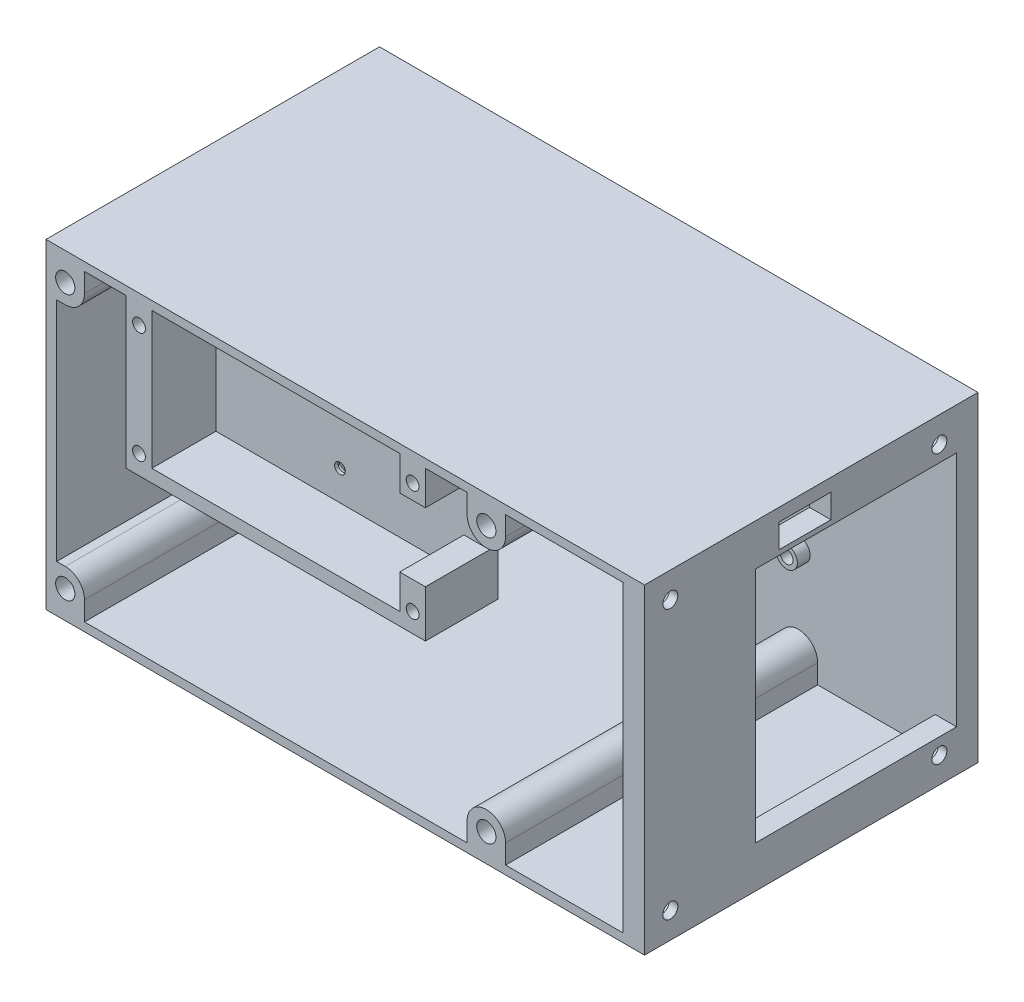
SolidWorks part; units mm, degrees
ref_plane "Płaszczyzna przednia" through (0, 0, 0) normal (0, 0, 1) x (1, 0, 0)
ref_plane "Płaszczyzna górna" through (0, 0, 0) normal (0, 1, 0) x (1, 0, 0)
ref_plane "Płaszczyzna prawa" through (0, 0, 0) normal (1, 0, 0) x (0, 0, -1)
sketch "Szkic1" plane through (0, 0, 0) normal (0, 0, 1) x (1, 0, 0)
  line L0 (0, 75) -> (140, 75)
  line L1 (140, 75) -> (140, 0)
  line L2 (140, 0) -> (0, 0)
  line L3 (0, 0) -> (0, 75)
  line L4 (3, 62.75) -> (3, 12.25) construction
  line L5 (3, 12.25) -> (73, 12.25) construction
  line L6 (73, 12.25) -> (73, 62.75) construction
  line L7 (73, 62.75) -> (3, 62.75) construction
  line L12 (70, 75) -> (70, 0) construction
  line L13 (0, 37.5) -> (140, 37.5) construction
  line L14 (88, 50.2) -> (88, 24.8) construction
  line L15 (88, 24.8) -> (105.78, 24.8) construction
  line L16 (105.78, 24.8) -> (105.78, 50.2) construction
  line L17 (105.78, 50.2) -> (88, 50.2) construction
  line L18 (96.89, 50.2) -> (96.89, 24.8) construction
  circle A0 centre (6.6, 58.05) radius 2
  circle A1 centre (6.6, 16.95) radius 2
  circle A2 centre (69.3, 58.05) radius 2
  circle A3 centre (69.3, 16.95) radius 2
  circle A4 centre (5.77, 45.35) radius 1 construction
  circle A5 centre (46.43, 45.35) radius 1 construction
  circle A6 centre (46.43, 30.09) radius 1 construction
  circle A7 centre (5.77, 30.09) radius 1 construction
  circle A17 centre (90.54, 47.66) radius 1.5
  circle A18 centre (103.24, 47.66) radius 1.5
  circle A19 centre (103.24, 27.34) radius 1.5
  circle A20 centre (90.54, 27.34) radius 1.5
  point P25 (73, 37.5)
  point P30 (88, 37.5)
  dimension "D5" = 4
  dimension "D9" = 2
  dimension "D17" = 3
  dimension "D21" = 3
  dimension "D3" = 70
  dimension "D4" = 50.5
  dimension "D6" = 3.6
  dimension "D7" = 4.7
  dimension "D8" = 4.7
  dimension "D10" = 3.7
  dimension "D11" = 4.7
  dimension "D12" = 43.43
  dimension "D13" = 2.77
  dimension "D14" = 17.4
  dimension "D15" = 32.66
  dimension "D16" = 140
  dimension "D18" = 25.4
  dimension "D19" = 17.78
  dimension "D20" = 15
  dimension "D22" = 6.35
  dimension "D23" = 10.16
  dimension "D26" = 75
extrude "Dodanie-wyciągnięcie1" add sketch "Szkic1" along normal blind 5
sketch "Szkic2" plane through (0, 0, 0) normal (0, 0, -1) x (-1, 0, 0)
  line L0 (-72.35, 59.8109) -> (-69.3, 61.5718)
  line L1 (-69.3, 61.5718) -> (-66.25, 59.8109)
  line L2 (-66.25, 59.8109) -> (-66.25, 56.2891)
  line L3 (-66.25, 56.2891) -> (-69.3, 54.5282)
  line L4 (-69.3, 54.5282) -> (-72.35, 56.2891)
  line L5 (-72.35, 56.2891) -> (-72.35, 59.8109)
  line L6 (-69.3, 58.05) -> (-69.3, 16.95) construction
  line L7 (-69.3, 16.95) -> (-6.6, 16.95) construction
  line L8 (-6.6, 16.95) -> (-6.6, 58.05) construction
  line L9 (-6.6, 58.05) -> (-69.3, 58.05) construction
  line L10 (-69.3, 37.5) -> (-6.6, 37.5) construction
  line L11 (-37.95, 58.05) -> (-37.95, 16.95) construction
  line L12 (-6.6, 54.5282) -> (-3.55, 56.2891)
  line L13 (-9.65, 56.2891) -> (-6.6, 54.5282)
  line L14 (-9.65, 59.8109) -> (-9.65, 56.2891)
  line L15 (-6.6, 61.5718) -> (-9.65, 59.8109)
  line L16 (-3.55, 59.8109) -> (-6.6, 61.5718)
  line L17 (-3.55, 56.2891) -> (-3.55, 59.8109)
  line L18 (-9.65, 18.7109) -> (-6.6, 20.4718)
  line L19 (-9.65, 15.1891) -> (-9.65, 18.7109)
  line L20 (-6.6, 13.4282) -> (-9.65, 15.1891)
  line L21 (-3.55, 15.1891) -> (-6.6, 13.4282)
  line L22 (-3.55, 18.7109) -> (-3.55, 15.1891)
  line L23 (-6.6, 20.4718) -> (-3.55, 18.7109)
  line L24 (-69.3, 20.4718) -> (-72.35, 18.7109)
  line L25 (-66.25, 18.7109) -> (-69.3, 20.4718)
  line L26 (-66.25, 15.1891) -> (-66.25, 18.7109)
  line L27 (-69.3, 13.4282) -> (-66.25, 15.1891)
  line L28 (-72.35, 15.1891) -> (-69.3, 13.4282)
  line L29 (-72.35, 18.7109) -> (-72.35, 15.1891)
  line L84 (-70, 75) -> (-70, 0) construction
  line L85 (-140, 75) -> (0, 75) construction
  line L86 (0, 0) -> (-140, 0) construction
  line L88 (-140, 37.5) -> (0, 37.5) construction
  line L89 (-140, 0) -> (-140, 75) construction
  line L90 (0, 75) -> (0, 0) construction
  line L91 (-93.09, 49.1322) -> (-90.54, 50.6045)
  line L92 (-90.54, 50.6045) -> (-87.99, 49.1322)
  line L93 (-87.99, 49.1322) -> (-87.99, 46.1878)
  line L94 (-87.99, 46.1878) -> (-90.54, 44.7155)
  line L95 (-90.54, 44.7155) -> (-93.09, 46.1878)
  line L96 (-93.09, 46.1878) -> (-93.09, 49.1322)
  line L97 (-90.54, 47.66) -> (-103.24, 47.66) construction
  line L98 (-103.24, 47.66) -> (-103.24, 27.34) construction
  line L99 (-103.24, 27.34) -> (-90.54, 27.34) construction
  line L100 (-90.54, 27.34) -> (-90.54, 47.66) construction
  line L102 (-96.89, 47.66) -> (-96.89, 27.34) construction
  line L104 (-103.24, 44.7155) -> (-100.69, 46.1878)
  line L105 (-105.79, 46.1878) -> (-103.24, 44.7155)
  line L106 (-105.79, 49.1322) -> (-105.79, 46.1878)
  line L107 (-103.24, 50.6045) -> (-105.79, 49.1322)
  line L108 (-100.69, 49.1322) -> (-103.24, 50.6045)
  line L109 (-100.69, 46.1878) -> (-100.69, 49.1322)
  line L110 (-90.54, 30.2845) -> (-93.09, 28.8122)
  line L111 (-87.99, 28.8122) -> (-90.54, 30.2845)
  line L112 (-90.54, 24.3955) -> (-87.99, 25.8678)
  line L113 (-87.99, 25.8678) -> (-87.99, 28.8122)
  line L114 (-93.09, 25.8678) -> (-90.54, 24.3955)
  line L115 (-93.09, 28.8122) -> (-93.09, 25.8678)
  line L116 (-105.79, 25.8678) -> (-105.79, 28.8122)
  line L117 (-103.24, 24.3955) -> (-105.79, 25.8678)
  line L118 (-100.69, 25.8678) -> (-103.24, 24.3955)
  line L119 (-100.69, 28.8122) -> (-100.69, 25.8678)
  line L120 (-103.24, 30.2845) -> (-100.69, 28.8122)
  line L121 (-105.79, 28.8122) -> (-103.24, 30.2845)
  circle A0 centre (-69.3, 58.05) radius 3.05 construction
  circle A1 centre (-69.3, 58.05) radius 2 construction
  circle A2 centre (-69.3, 16.95) radius 2 construction
  circle A3 centre (-6.6, 16.95) radius 2 construction
  circle A4 centre (-6.6, 58.05) radius 2 construction
  circle A5 centre (-69.3, 16.95) radius 2
  circle A6 centre (-6.6, 16.95) radius 2
  circle A7 centre (-6.6, 58.05) radius 2
  circle A8 centre (-69.3, 58.05) radius 2
  circle A9 centre (-90.54, 47.66) radius 2.55 construction
  circle A11 centre (-90.54, 47.66) radius 1.5 construction
  circle A12 centre (-90.54, 47.66) radius 1.5
  circle A13 centre (-90.54, 27.34) radius 1.5 construction
  circle A14 centre (-103.24, 27.34) radius 1.5 construction
  circle A15 centre (-103.24, 47.66) radius 1.5 construction
  circle A16 centre (-90.54, 27.34) radius 1.5
  circle A17 centre (-103.24, 27.34) radius 1.5
  circle A18 centre (-103.24, 47.66) radius 1.5
  dimension "D1" = 6.1
  dimension "D2" = 5.1
extrude "Wytnij-wyciągnięcie1" cut sketch "Szkic2" against normal blind 3
sketch "Szkic4" plane through (0, 0, 5) normal (0, 0, 1) x (1, 0, 0)
  circle A0 centre (90.54, 27.34) radius 1.5 construction
  circle A1 centre (103.24, 27.34) radius 1.5 construction
  circle A2 centre (103.24, 47.66) radius 1.5 construction
  circle A3 centre (90.54, 47.66) radius 1.5 construction
  circle A4 centre (69.3, 16.95) radius 2 construction
  circle A5 centre (69.3, 58.05) radius 2 construction
  circle A6 centre (6.6, 16.95) radius 2 construction
  circle A7 centre (6.6, 58.05) radius 2 construction
  circle A12 centre (69.3, 16.95) radius 2
  circle A13 centre (69.3, 58.05) radius 2
  circle A14 centre (6.6, 16.95) radius 2
  circle A15 centre (6.6, 58.05) radius 2
  circle A16 centre (6.6, 58.05) radius 4
  circle A17 centre (69.3, 58.05) radius 4
  circle A18 centre (6.6, 16.95) radius 4
  circle A19 centre (69.3, 16.95) radius 4
  circle A20 centre (90.54, 27.34) radius 1.5
  circle A21 centre (103.24, 27.34) radius 1.5
  circle A22 centre (103.24, 47.66) radius 1.5
  circle A23 centre (90.54, 47.66) radius 1.5
  circle A24 centre (90.54, 47.66) radius 2.5
  circle A25 centre (103.24, 47.66) radius 2.5
  circle A26 centre (90.54, 27.34) radius 2.5
  circle A27 centre (103.24, 27.34) radius 2.5
  dimension "D1" = 8
  dimension "D2" = 5
extrude "Dodanie-wyciągnięcie3" add sketch "Szkic4" along normal blind 3
sketch "Szkic7" plane through (0, 0, 5) normal (0, 0, 1) x (1, 0, 0)
  line L0 (140, 75) -> (0, 75) construction
  line L1 (140, 0) -> (140, 75) construction
  line L2 (0, 0) -> (140, 0) construction
  line L4 (140, 75) -> (0, 75)
  line L5 (140, 0) -> (140, 75)
  line L6 (0, 0) -> (140, 0)
  line L8 (135, 73) -> (2, 73)
  line L10 (2, 2) -> (135, 2)
  line L12 (2, 73) -> (0, 73)
  line L13 (2, 2) -> (0, 2)
  line L14 (0, 75) -> (0, 73)
  line L15 (0, 75) -> (0, 0) construction
  line L16 (0, 2) -> (0, 0)
  line L17 (9, 68.5) -> (9, 73)
  line L18 (2, 73) -> (2, 2) construction
  line L19 (4.5, 64) -> (0, 64)
  line L20 (0, 37.5) -> (138, 37.5) construction
  line L21 (0, 75) -> (0, 0) construction
  line L22 (0, 64) -> (0, 73)
  line L23 (9, 6.5) -> (9, 2)
  line L24 (98.5, 68.5) -> (98.5, 73)
  line L25 (107.5, 68.5) -> (107.5, 73)
  line L26 (4.5, 11) -> (0, 11)
  line L27 (0, 11) -> (0, 2)
  line L28 (107.5, 6.5) -> (107.5, 2)
  line L29 (98.5, 6.5) -> (98.5, 2)
  line L30 (135, 73) -> (135, 2)
  line L31 (2, 2) -> (138, 2) construction
  line L32 (138, 2) -> (138, 73) construction
  line L33 (138, 73) -> (2, 73) construction
  line L34 (2.5, 64) -> (2.5, 11)
  line L35 (0, 64) -> (0, 11)
  circle A1 centre (4.5, 68.5) radius 4.5 construction
  arc A2 (4.5, 64) -> (9, 68.5) centre (4.5, 68.5) ccw
  arc A3 (4.5, 11) -> (9, 6.5) centre (4.5, 6.5) cw
  circle A4 centre (103, 68.5) radius 4.5 construction
  arc A5 (98.5, 68.5) -> (107.5, 68.5) centre (103, 68.5) ccw
  arc A6 (98.5, 6.5) -> (107.5, 6.5) centre (103, 6.5) cw
  dimension "D2" = 9
  dimension "D3" = 32
  dimension "D4" = 5
  dimension "D5" = 2.5
  dimension "D1" = 2
extrude "Dodanie-wyciągnięcie5" add sketch "Szkic7" along normal blind 73
sketch "Szkic8" plane through (140, 0, 0) normal (1, 0, 0) x (0, 0, -1)
  line L0 (-52, 65.25) -> (-5, 65.25)
  line L1 (-5, 65.25) -> (-5, 9.75)
  line L2 (-5, 9.75) -> (-52, 9.75)
  line L3 (-52, 9.75) -> (-52, 65.25)
  line L4 (-78, 0) -> (-78, 75) construction
  line L5 (0, 0) -> (0, 75) construction
  point P6 (-78, 37.5)
  point P7 (-5, 37.5)
  dimension "D1" = 26
  dimension "D2" = 55.5
  dimension "D3" = 5
extrude "Wytnij-wyciągnięcie2" cut sketch "Szkic8" against normal up to next
sketch "Szkic9" plane through (0, 0, 78) normal (0, 0, 1) x (1, 0, 0)
  circle A0 centre (4.5, 68.5) radius 2.25
  arc A1 (4.5, 64) -> (9, 68.5) centre (4.5, 68.5) ccw construction
  circle A2 centre (103, 68.5) radius 2.25
  circle A3 centre (4.5, 6.5) radius 2.25
  circle A4 centre (103, 6.5) radius 2.25
  arc A5 (9, 6.5) -> (4.5, 11) centre (4.5, 6.5) ccw construction
  arc A6 (107.5, 6.5) -> (98.5, 6.5) centre (103, 6.5) ccw construction
  arc A7 (98.5, 68.5) -> (107.5, 68.5) centre (103, 68.5) ccw construction
  dimension "D1" = 4.5
extrude "Wytnij-wyciągnięcie3" cut sketch "Szkic9" against normal through all
sketch "Szkic10" plane through (0, 0, 0) normal (0, 0, -1) x (-1, 0, 0)
  line L0 (-106.55, 70.5496) -> (-103, 72.5992)
  line L1 (-103, 72.5992) -> (-99.45, 70.5496)
  line L2 (-99.45, 70.5496) -> (-99.45, 66.4504)
  line L3 (-99.45, 66.4504) -> (-103, 64.4008)
  line L4 (-103, 64.4008) -> (-106.55, 66.4504)
  line L5 (-106.55, 66.4504) -> (-106.55, 70.5496)
  line L6 (-103, 68.5) -> (-103, 6.5) construction
  line L7 (-103, 6.5) -> (-4.5, 6.5) construction
  line L8 (-4.5, 6.5) -> (-4.5, 68.5) construction
  line L9 (-4.5, 68.5) -> (-103, 68.5) construction
  line L10 (-53.75, 6.5) -> (-53.75, 68.5) construction
  line L11 (-103, 37.5) -> (-4.5, 37.5) construction
  line L12 (-99.45, 8.5496) -> (-103, 10.5992)
  line L13 (-99.45, 4.4504) -> (-99.45, 8.5496)
  line L14 (-103, 2.4008) -> (-99.45, 4.4504)
  line L15 (-106.55, 4.4504) -> (-103, 2.4008)
  line L16 (-106.55, 8.5496) -> (-106.55, 4.4504)
  line L17 (-103, 10.5992) -> (-106.55, 8.5496)
  line L18 (-4.5, 64.4008) -> (-0.95, 66.4504)
  line L19 (-8.05, 66.4504) -> (-4.5, 64.4008)
  line L20 (-8.05, 70.5496) -> (-8.05, 66.4504)
  line L21 (-4.5, 72.5992) -> (-8.05, 70.5496)
  line L22 (-0.95, 70.5496) -> (-4.5, 72.5992)
  line L23 (-0.95, 66.4504) -> (-0.95, 70.5496)
  line L24 (-0.95, 4.4504) -> (-4.5, 2.4008)
  line L25 (-4.5, 2.4008) -> (-8.05, 4.4504)
  line L26 (-8.05, 4.4504) -> (-8.05, 8.5496)
  line L27 (-8.05, 8.5496) -> (-4.5, 10.5992)
  line L28 (-4.5, 10.5992) -> (-0.95, 8.5496)
  line L29 (-0.95, 8.5496) -> (-0.95, 4.4504)
  circle A0 centre (-103, 68.5) radius 3.55 construction
  circle A1 centre (-103, 68.5) radius 2.25 construction
  point P26 (-101.225, 9.5744)
  point P27 (-101.225, 3.4256)
  point P36 (-6.275, 3.4256)
  point P39 (-6.275, 9.5744)
  dimension "D1" = 7.1
extrude "Wytnij-wyciągnięcie4" cut sketch "Szkic10" against normal blind 47
sketch "Szkic12" plane through (0, 73, 0) normal (0, -1, 0) x (1, 0, 0)
  line L0 (18.75, 61) -> (88.75, 61)
  line L1 (88.75, 61) -> (88.75, 63)
  line L2 (88.75, 63) -> (18.75, 63)
  line L3 (18.75, 63) -> (18.75, 61)
  line L4 (98.5, 78) -> (9, 78) construction
  line L5 (9, 61) -> (98.5, 61) construction
  line L6 (9, 78) -> (9, 5) construction
  line L7 (98.5, 78) -> (98.5, 5) construction
  point P12 (53.75, 61)
  point P13 (53.75, 61)
  dimension "D1" = 70
  dimension "D2" = 2
  dimension "D3" = 15
extrude "Dodanie-wyciągnięcie6" add sketch "Szkic12" along normal blind 35
sketch "Szkic13" plane through (0, 0, 63) normal (0, 0, 1) x (1, 0, 0)
  line L0 (24.75, 73) -> (82.75, 73) construction
  line L1 (82.75, 73) -> (82.75, 41) construction
  line L2 (82.75, 41) -> (24.75, 41)
  line L3 (24.75, 41) -> (24.75, 73)
  line L4 (98.5, 73) -> (9, 73) construction
  line L5 (88.75, 38) -> (18.75, 38) construction
  line L6 (82.75, 41) -> (82.75, 49)
  line L7 (82.75, 73) -> (82.75, 65)
  line L8 (88.75, 73) -> (18.75, 73) construction
  line L9 (88.75, 38) -> (88.75, 73) construction
  line L10 (18.75, 38) -> (18.75, 73) construction
  line L11 (88.75, 73) -> (18.75, 73)
  line L12 (88.75, 38) -> (88.75, 73)
  line L13 (88.75, 38) -> (18.75, 38)
  line L14 (18.75, 38) -> (18.75, 73)
  line L15 (82.75, 65) -> (88.75, 65)
  line L16 (82.75, 49) -> (88.75, 49)
  point P8 (53.75, 38)
  point P9 (53.75, 41)
  line M4 (88.75, 73) -> (18.75, 73)
  line M5 (18.75, 73) -> (18.75, 38)
  line M6 (18.75, 38) -> (88.75, 38)
  line M7 (88.75, 38) -> (88.75, 73)
  dimension "D1" = 58
  dimension "D2" = 32
  dimension "D3" = 8
extrude "Dodanie-wyciągnięcie7" add sketch "Szkic13" along normal blind 15 contours L16 L6 L2 L3 M4 M5 M6 M7 | L7 L15 L12 M4
sketch "Szkic14" plane through (0, 0, 63) normal (0, 0, 1) x (1, 0, 0)
  line L0 (82.75, 41) -> (24.75, 41) construction
  line L1 (53.75, 41) -> (53.75, 73) construction
  line L2 (82.75, 73) -> (24.75, 73) construction
  line L3 (24.75, 57) -> (88.75, 57) construction
  line L4 (24.75, 41) -> (24.75, 73) construction
  line L5 (88.75, 49) -> (88.75, 65) construction
  circle A0 centre (53.75, 66) radius 1.25
  circle A1 centre (53.75, 48) radius 1.25
  dimension "D1" = 2.5
  dimension "D2" = 7
extrude "Wytnij-wyciągnięcie5" cut sketch "Szkic14" against normal up to next
sketch "Szkic15" plane through (0, 0, 61) normal (0, 0, -1) x (-1, 0, 0)
  line L0 (-55.9, 49.2413) -> (-53.75, 50.4826)
  line L1 (-53.75, 50.4826) -> (-51.6, 49.2413)
  line L2 (-51.6, 49.2413) -> (-51.6, 46.7587)
  line L3 (-51.6, 46.7587) -> (-53.75, 45.5174)
  line L4 (-53.75, 45.5174) -> (-55.9, 46.7587)
  line L5 (-55.9, 46.7587) -> (-55.9, 49.2413)
  line L6 (-53.6617, 48) -> (-53.75, 48)
  line L9 (-53.75, 48) -> (-53.75, 66) construction
  line L10 (-88.75, 57) -> (-18.75, 57) construction
  line L11 (-88.75, 38) -> (-88.75, 73) construction
  line L12 (-18.75, 38) -> (-18.75, 73) construction
  line L13 (-51.6, 64.7587) -> (-51.6, 67.2413)
  line L14 (-51.6, 67.2413) -> (-53.75, 68.4826)
  line L15 (-53.75, 68.4826) -> (-55.9, 67.2413)
  line L16 (-55.9, 67.2413) -> (-55.9, 64.7587)
  line L17 (-53.75, 63.5174) -> (-51.6, 64.7587)
  line L18 (-55.9, 64.7587) -> (-53.75, 63.5174)
  circle A0 centre (-53.75, 48) radius 2.15 construction
  circle A1 centre (-53.75, 48) radius 1.25 construction
  point P14 (-53.75, 57)
  circle M10 centre (-53.75, 66) radius 1.25
  circle M11 centre (-53.75, 48) radius 1.25
  dimension "D1" = 4.3
extrude "Wytnij-wyciągnięcie6" cut sketch "Szkic15" against normal blind 1.2 contours L5 L4 L3 L2 L1 L0 M11 | L16 L18 L17 L13 L14 L15 M10
sketch "Szkic16" plane through (0, 0, 78) normal (0, 0, 1) x (1, 0, 0)
  line L0 (88.75, 65) -> (88.75, 73) construction
  line L1 (88.75, 38) -> (88.75, 49) construction
  line L2 (18.75, 73) -> (18.75, 38) construction
  line L3 (18.75, 38) -> (88.75, 38) construction
  line L4 (88.75, 65) -> (88.75, 73) construction
  line L5 (88.75, 38) -> (88.75, 49) construction
  line L6 (18.75, 73) -> (18.75, 38) construction
  line L7 (18.75, 38) -> (88.75, 38) construction
  line L8 (24.75, 41) -> (24.75, 73) construction
  line L9 (24.75, 41) -> (24.75, 73) construction
  line L10 (21.75, 68.5) -> (21.75, 42.5) construction
  line L11 (18.75, 55.5) -> (24.75, 55.5) construction
  line L12 (85.75, 49) -> (85.75, 38) construction
  line L13 (82.75, 49) -> (88.75, 49) construction
  circle A0 centre (21.75, 68.5) radius 1.5
  circle A1 centre (21.75, 42.5) radius 1.5
  circle A2 centre (85.75, 42.5) radius 1.5
  circle A3 centre (85.75, 68.5) radius 1.5
  point P18 (21.75, 55.5)
  point P19 (21.75, 55.5)
  dimension "D1" = 3
  dimension "D2" = 26
extrude "Wytnij-wyciągnięcie7" cut sketch "Szkic16" against normal up to next
sketch "Szkic18" plane through (0, 0, 61) normal (0, 0, -1) x (-1, 0, 0)
  line L0 (-24.25, 43.9434) -> (-21.75, 45.3868)
  line L1 (-21.75, 45.3868) -> (-19.25, 43.9434)
  line L2 (-19.25, 43.9434) -> (-19.25, 41.0566)
  line L3 (-19.25, 41.0566) -> (-21.75, 39.6132)
  line L4 (-21.75, 39.6132) -> (-24.25, 41.0566)
  line L5 (-24.25, 41.0566) -> (-24.25, 43.9434)
  line L6 (-21.75, 42.5) -> (-85.75, 42.5) construction
  line L7 (-85.75, 42.5) -> (-85.75, 68.5) construction
  line L8 (-85.75, 68.5) -> (-21.75, 68.5) construction
  line L15 (-21.75, 68.5) -> (-21.75, 42.5) construction
  line L16 (-85.75, 55.5) -> (-21.75, 55.5) construction
  line L17 (-53.75, 68.5) -> (-53.75, 42.5) construction
  line L18 (-24.25, 69.9434) -> (-24.25, 67.0566)
  line L19 (-21.75, 71.3868) -> (-24.25, 69.9434)
  line L20 (-19.25, 69.9434) -> (-21.75, 71.3868)
  line L21 (-19.25, 67.0566) -> (-19.25, 69.9434)
  line L22 (-21.75, 65.6132) -> (-19.25, 67.0566)
  line L23 (-24.25, 67.0566) -> (-21.75, 65.6132)
  line L24 (-83.25, 41.0566) -> (-83.25, 43.9434)
  line L25 (-85.75, 39.6132) -> (-83.25, 41.0566)
  line L26 (-88.25, 41.0566) -> (-85.75, 39.6132)
  line L27 (-88.25, 43.9434) -> (-88.25, 41.0566)
  line L28 (-85.75, 45.3868) -> (-88.25, 43.9434)
  line L29 (-83.25, 43.9434) -> (-85.75, 45.3868)
  line L30 (-83.25, 69.9434) -> (-83.25, 67.0566)
  line L31 (-83.25, 67.0566) -> (-85.75, 65.6132)
  line L32 (-85.75, 65.6132) -> (-88.25, 67.0566)
  line L33 (-88.25, 67.0566) -> (-88.25, 69.9434)
  line L34 (-88.25, 69.9434) -> (-85.75, 71.3868)
  line L35 (-85.75, 71.3868) -> (-83.25, 69.9434)
  circle A0 centre (-21.75, 42.5) radius 2.5 construction
  circle A1 centre (-85.75, 42.5) radius 1.5 construction
  circle A2 centre (-21.75, 42.5) radius 1.5 construction
  circle A3 centre (-21.75, 68.5) radius 1.5 construction
  circle A4 centre (-85.75, 68.5) radius 1.5 construction
  circle A5 centre (-85.75, 42.5) radius 1.5
  circle A6 centre (-21.75, 42.5) radius 1.5
  circle A7 centre (-21.75, 68.5) radius 1.5
  circle A8 centre (-85.75, 68.5) radius 1.5
  dimension "D1" = 5
extrude "Wytnij-wyciągnięcie8" cut sketch "Szkic18" against normal blind 13
sketch "Szkic20" plane through (140, 0, 0) normal (1, 0, 0) x (0, 0, -1)
  line L0 (-85, 37.5) -> (4, 37.5) construction
  line L1 (-71.9663, 68.9663) -> (-9.0337, 6.0337) construction
  line L2 (-71.9663, 6.0337) -> (-9.0337, 68.9663) construction
  line L3 (0, 0) -> (0, 75) construction
  circle A0 centre (-40.5, 37.5) radius 44.5 construction
  circle A1 centre (-71.9663, 68.9663) radius 1.75
  circle A2 centre (-9.0337, 68.9663) radius 1.75
  circle A3 centre (-9.0337, 6.0337) radius 1.75
  circle A4 centre (-71.9663, 6.0337) radius 1.75
  point P16 (0, 37.5)
  dimension "D1" = 89
  dimension "D3" = 3.5
  dimension "D2" = 45
  dimension "D4" = 40.5
extrude "Wytnij-wyciągnięcie9" cut sketch "Szkic20" against normal up to next
sketch "Szkic21" plane through (135, 0, 0) normal (-1, 0, 0) x (0, 0, 1)
  line L0 (68.9663, 7.7658) -> (71.9663, 9.4978)
  line L1 (71.9663, 9.4978) -> (74.9663, 7.7658)
  line L2 (74.9663, 7.7658) -> (74.9663, 4.3017)
  line L3 (74.9663, 4.3017) -> (71.9663, 2.5696)
  line L4 (71.9663, 2.5696) -> (68.9663, 4.3017)
  line L5 (68.9663, 4.3017) -> (68.9663, 7.7658)
  line L6 (78, 37.5) -> (52, 37.5) construction
  line L7 (78, 73) -> (78, 2) construction
  line L8 (52, 9.75) -> (52, 65.25) construction
  line L9 (71.9663, 65.5022) -> (74.9663, 67.2342)
  line L10 (74.9663, 67.2342) -> (74.9663, 70.6983)
  line L11 (71.9663, 72.4304) -> (68.9663, 70.6983)
  line L12 (74.9663, 70.6983) -> (71.9663, 72.4304)
  line L13 (68.9663, 70.6983) -> (68.9663, 67.2342)
  line L14 (68.9663, 67.2342) -> (71.9663, 65.5022)
  line L15 (71.9663, 68.9663) -> (9.0337, 68.9663) construction
  line L16 (9.0337, 6.0337) -> (71.9663, 6.0337) construction
  line L17 (40.5, 68.9663) -> (40.5, 6.0337) construction
  line L18 (6.0337, 70.6983) -> (9.0337, 72.4304)
  line L19 (6.0337, 67.2342) -> (6.0337, 70.6983)
  line L20 (9.0337, 65.5022) -> (6.0337, 67.2342)
  line L21 (12.0337, 67.2342) -> (9.0337, 65.5022)
  line L22 (9.0337, 72.4304) -> (12.0337, 70.6983)
  line L23 (12.0337, 70.6983) -> (12.0337, 67.2342)
  line L24 (6.0337, 4.3017) -> (9.0337, 2.5696)
  line L25 (6.0337, 7.7658) -> (6.0337, 4.3017)
  line L26 (9.0337, 9.4978) -> (6.0337, 7.7658)
  line L27 (9.0337, 2.5696) -> (12.0337, 4.3017)
  line L28 (12.0337, 4.3017) -> (12.0337, 7.7658)
  line L29 (12.0337, 7.7658) -> (9.0337, 9.4978)
  circle A0 centre (71.9663, 6.0337) radius 3 construction
  point P29 (70.4663, 71.5643)
  point P35 (10.5337, 71.5643)
  dimension "D1" = 6
extrude "Wytnij-wyciągnięcie10" cut sketch "Szkic21" against normal blind 3 and the other way blind 5
sketch "Szkic22" plane through (0, 0, 0) normal (-1, 0, 0) x (0, 0, 1)
  line L0 (19.7, 34.5) -> (19.7, 40.5)
  line L1 (22.7, 40.5) -> (22.7, 34.5)
  line L2 (21.2, 42) -> (21.2, 33) construction
  line L3 (19.7, 37.5) -> (22.7, 37.5) construction
  line L4 (0, 75) -> (0, 0) construction
  arc A0 (19.7, 40.5) -> (22.7, 40.5) centre (21.2, 40.5) cw
  arc A1 (22.7, 34.5) -> (19.7, 34.5) centre (21.2, 34.5) cw
  point P6 (0, 37.5)
  dimension "D1" = 9
  dimension "D2" = 3
  dimension "D3" = 19.7
extrude "Wytnij-wyciągnięcie11" cut sketch "Szkic22" against normal up to next
sketch "Szkic23" plane through (0, 0, 0) normal (-1, 0, 0) x (0, 0, 1)
  line L0 (22.7, 34.5) -> (22.7, 40.5) construction
  line L1 (19.7, 40.5) -> (19.7, 34.5) construction
  line L2 (22.7, 34.5) -> (22.7, 40.5)
  line L3 (19.7, 40.5) -> (19.7, 34.5)
  line L4 (17.7, 40.5) -> (17.7, 34.5)
  line L5 (24.7, 34.5) -> (24.7, 40.5)
  arc A0 (19.7, 34.5) -> (22.7, 34.5) centre (21.2, 34.5) ccw construction
  arc A1 (22.7, 40.5) -> (19.7, 40.5) centre (21.2, 40.5) ccw construction
  arc A2 (19.7, 34.5) -> (22.7, 34.5) centre (21.2, 34.5) ccw
  arc A3 (22.7, 40.5) -> (19.7, 40.5) centre (21.2, 40.5) ccw
  arc A4 (17.7, 34.5) -> (24.7, 34.5) centre (21.2, 34.5) ccw
  arc A5 (24.7, 40.5) -> (17.7, 40.5) centre (21.2, 40.5) ccw
  dimension "D1" = 2
extrude "Wytnij-wyciągnięcie12" cut sketch "Szkic23" against normal blind 2.1
sketch "Szkic24" plane through (140, 0, 0) normal (1, 0, 0) x (0, 0, -1)
  line L0 (-46.6, 72) -> (-46.6, 66.4)
  line L1 (-46.6, 66.4) -> (-34.4, 66.4)
  line L2 (-34.4, 66.4) -> (-34.4, 72)
  line L3 (-34.4, 72) -> (-46.6, 72)
  line L4 (-78, 75) -> (0, 75) construction
  line L5 (0, 0) -> (0, 75) construction
  dimension "D1" = 3
  dimension "D2" = 12.2
  dimension "D3" = 5.6
  dimension "D4" = 34.4
extrude "Wytnij-wyciągnięcie13" cut sketch "Szkic24" against normal up to next
equation "\"PrintAllowance\"= 0.1"
equation "\"M3NutDiameter\"= 6 + \"PrintAllowance\""
equation "\"D1@Szkic2\"= \"M3NutDiameter\""
equation "\"M2_5NutDiameter\"= 5 + \"PrintAllowance\""
equation "\"D2@Szkic2\"= \"M2_5NutDiameter\""
